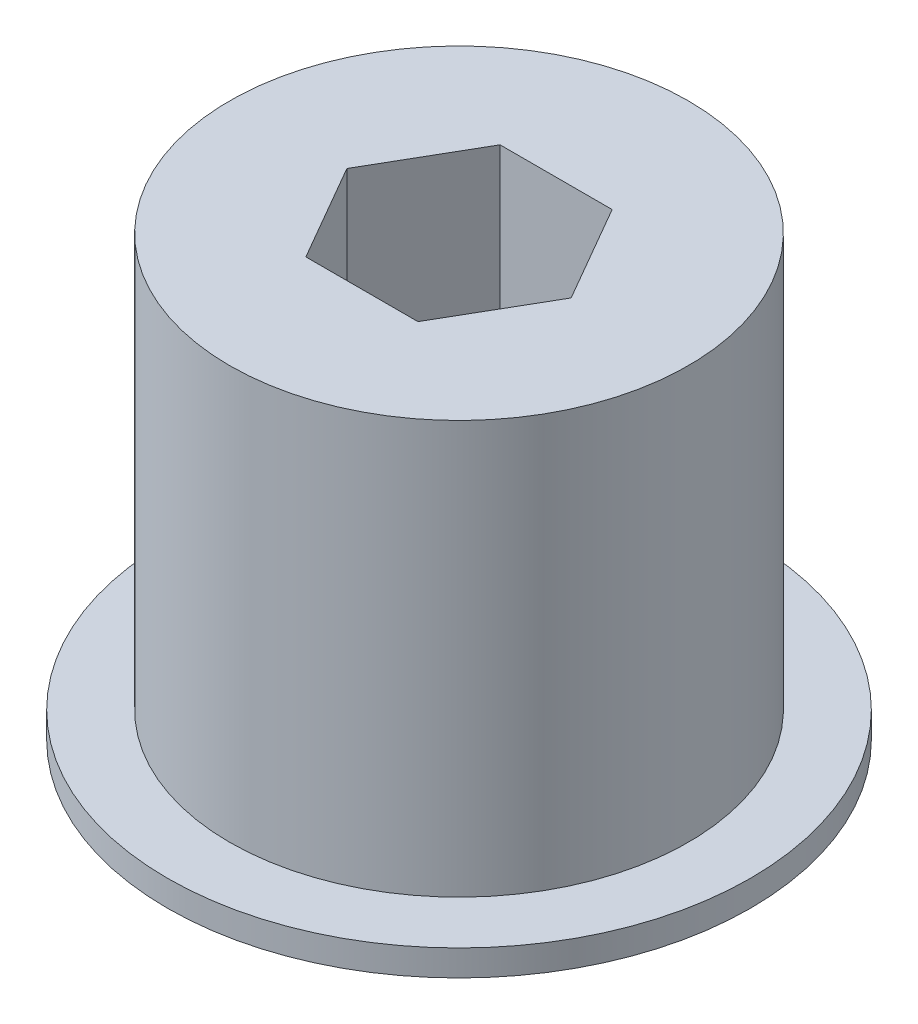
SolidWorks part; units mm, degrees
ref_plane "Front Plane" through (0, 0, 0) normal (0, 0, 1) x (1, 0, 0)
ref_plane "Top Plane" through (0, 0, 0) normal (0, 1, 0) x (1, 0, 0)
ref_plane "Right Plane" through (0, 0, 0) normal (1, 0, 0) x (0, 0, -1)
sketch "Sketch1" plane through (0, 0, 0) normal (0, 1, 0) x (1, 0, 0)
  circle A0 centre (0, 0) radius 15
  dimension "D1" = 30
extrude "Boss-Extrude1" add sketch "Sketch1" along normal blind 27
sketch "Sketch2" plane through (0, 0, 0) normal (0, -1, 0) x (1, 0, 0)
  circle A0 centre (0, 0) radius 19.07
  dimension "D1" = 38.14
extrude "Boss-Extrude2" add sketch "Sketch2" along normal blind 1.7
sketch "Sketch3" plane through (0, -1.7, 0) normal (0, -1, 0) x (1, 0, 0)
  line L1 (-3.6662, 6.35) -> (-7.3323, 0)
  line L2 (-7.3323, 0) -> (-3.6662, -6.35)
  line L3 (-3.6662, -6.35) -> (3.6662, -6.35)
  line L4 (3.6662, -6.35) -> (7.3323, 0)
  line L5 (7.3323, 0) -> (3.6662, 6.35)
  line L6 (3.6662, 6.35) -> (-3.6662, 6.35)
  circle A0 centre (0, 0) radius 6.35 construction
  dimension "D1" = 12.7
extrude "Cut-Extrude1" cut sketch "Sketch3" against normal through all
